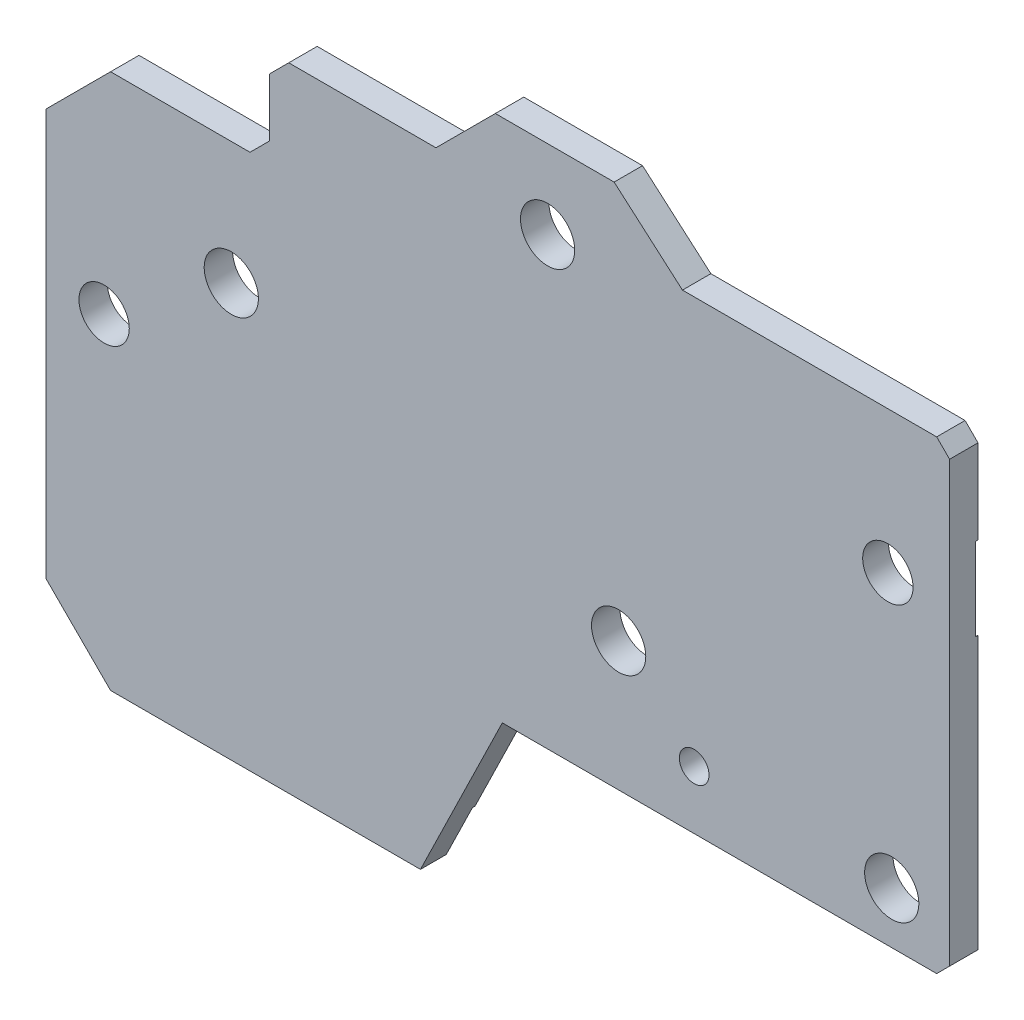
SolidWorks part; units mm, degrees
ref_plane "정면" through (0, 0, 0) normal (0, 0, 1) x (1, 0, 0)
ref_plane "윗면" through (0, 0, 0) normal (0, 1, 0) x (1, 0, 0)
ref_plane "우측면" through (0, 0, 0) normal (1, 0, 0) x (0, 0, -1)
sketch "스케치1" plane through (0, 0, 0) normal (0, 0, 1) x (1, 0, 0)
  line L0 (36.5, 0) -> (42.8405, 13)
  line L1 (42.3, 53.6) -> (51.5, 53.6)
  line L2 (0, 37.1) -> (0, 0)
  line L3 (0, 0) -> (36.5, 0)
  line L4 (72.0417, 49) -> (77.4805, 49)
  line L5 (42.8405, 13) -> (77.4805, 13)
  line L6 (77.4805, 49) -> (77.4805, 43.5612)
  line L8 (11.9, 49) -> (0, 37.1)
  line L9 (72.0417, 49) -> (77.4805, 43.5612) construction
  line L10 (42.3, 53.6) -> (37.7, 49)
  line L11 (37.7, 49) -> (11.9, 49)
  line L12 (51.5, 53.6) -> (56.7917, 49)
  line L13 (56.7917, 49) -> (72.0417, 49)
  line L14 (56.7917, 49) -> (11.9, 49) construction
  line L17 (77.4805, 13) -> (77.4805, 43.5612)
  circle A0 centre (21.85, 32) radius 2.1
  circle A1 centre (46.35, 47.5) radius 2.1
  circle A2 centre (51.85, 23) radius 2.1
  circle A3 centre (12, 25) radius 4.2
  circle A4 centre (12, 25) radius 2.5
  circle A5 centre (57.7, 17.5) radius 2.7
  circle A6 centre (57.7, 17.5) radius 1.15
  circle A7 centre (73, 17) radius 2.1
  point P0 (-1.1998, -0.6969)
  dimension "D1" = 4.2
  dimension "D2" = 4.2
  dimension "D3" = 4.2
  dimension "D9" = 2.3
  dimension "D10" = 5.4
  dimension "D11" = 5
  dimension "D12" = 8.4
  dimension "D13" = 12
  dimension "D31" = 4.2
  dimension "D4" = 24.5
  dimension "D5" = 24.5
  dimension "D6" = 30
  dimension "D7" = 15.5
  dimension "D8" = 9
  dimension "D14" = 25
  dimension "D15" = 34.64
  dimension "D16" = 135
  dimension "D17" = 13
  dimension "D18" = 49
  dimension "D19" = 4.6
  dimension "D20" = 9.2
  dimension "D21" = 41
  dimension "D22" = 15.25
  dimension "D23" = 57.7
  dimension "D24" = 37.1
  dimension "D25" = 135
  dimension "D26" = 17.5
  dimension "D27" = 25.8
  dimension "D28" = 135
  dimension "D29" = 36.5
  dimension "D30" = 116
  dimension "D32" = 32
  dimension "D33" = 21.85
  dimension "D34" = 73
  dimension "D35" = 17
extrude "보스-돌출1" add sketch "스케치1" along normal blind 3.2
sketch "스케치3" plane through (0, 0, 3.2) normal (0, 0, 1) x (1, 0, 0)
  circle A0 centre (12, 25) radius 4.2 construction
  circle A1 centre (12, 25) radius 4.2
  circle A2 centre (12, 25) radius 1.95
  circle A3 centre (57.7, 17.5) radius 2.7 construction
  circle A4 centre (57.7, 17.5) radius 2.7
  circle A5 centre (57.7, 17.5) radius 1.15
  dimension "D1" = 3.9
  dimension "D2" = 2.3
extrude "보스-돌출3" add sketch "스케치3" against normal blind 3.2
sketch "스케치6" plane through (0, 0, 3.2) normal (0, 0, 1) x (1, 0, 0)
  line L0 (44.2587, 8.0587) -> (101.1413, 8.0587) construction
  line L1 (102.1413, 9.0587) -> (102.1413, 65.9413) construction
  line L2 (101.1413, 66.9413) -> (72.7, 66.9413) construction
  line L3 (43.2587, 9.0587) -> (43.2587, 37.5) construction
  line L6 (37.7, 49) -> (11.9, 49) construction
  line L7 (0, 37.1) -> (0, 0) construction
  arc A0 (72.7, 66.9413) -> (43.2587, 37.5) centre (72.7, 37.5) ccw construction
  arc A1 (44.2587, 8.0587) -> (43.2587, 9.0587) centre (44.2587, 9.0587) cw construction
  arc A2 (101.1413, 8.0587) -> (102.1413, 9.0587) centre (101.1413, 9.0587) ccw construction
  arc A3 (102.1413, 65.9413) -> (101.1413, 66.9413) centre (101.1413, 65.9413) ccw construction
  dimension "D1" = 1
  dimension "D2" = 72.7
  dimension "D3" = 11.5
sketch "스케치7" plane through (0, 0, 0) normal (0, 0, -1) x (-1, 0, 0)
  circle A8 centre (-35, 4) radius 2.5
  circle A9 centre (-36.9, 49) radius 2.5
  circle A15 centre (-35, 4) radius 2.65
  dimension "D2" = 5
  dimension "D5" = 5
extrude "컷-돌출1" cut sketch "스케치7" against normal blind 1
chamfer "모따기1" distance 1 angle 45 1 edges at (0, 0, 2.1)
sketch "스케치11" plane through (0, 0, 3.2) normal (0, 0, 1) x (1, 0, 0)
  point P1 (72.7, 37.5)
  point P2 (57.7, 17.5)
  point P3 (12, 25)
chamfer "모따기3" distance 1 angle 45 1 edges at (77.4805, 13, 2.1)
sketch "스케치12" plane through (0, 0, 1) normal (0, 0, -1) x (-1, 0, 0)
  circle A0 centre (-6.5, 5) radius 2.1 construction
  circle A1 centre (-72.7, 38) radius 1.95
  dimension "D3" = 4.2
  dimension "D4" = 3.9
  dimension "D1" = 6.5
  dimension "D2" = 5
  dimension "D5" = 72.7
  dimension "D6" = 38
extrude "컷-돌출2" cut sketch "스케치12" against normal blind 10
sketch "스케치13" plane through (0, 0, 0) normal (0, 0, 1) x (1, 0, 0)
  line L0 (24.8, 49) -> (24.8, 41.5)
  line L1 (24.8, 41.5) -> (0, 41.5)
  line L2 (0, 41.5) -> (0, 49)
  line L3 (0, 49) -> (24.8, 49)
  line L4 (11.9, 49) -> (37.7, 49) construction
  dimension "D1" = 7.5
extrude "컷-돌출3" cut sketch "스케치13" along normal blind 10
chamfer "모따기4" distance 1.5 angle 45 2 edges at (24.8, 49, 2.1) (24.8, 41.5, 2.1)
sketch "스케치14" plane through (0, 0, 1) normal (0, 0, -1) x (-1, 0, 0)
  circle A0 centre (-6.5, 5) radius 5.05
  dimension "D1" = 10.1
  dimension "D2" = 6.5
  dimension "D3" = 5
extrude "컷-돌출4" [suppressed] cut sketch "스케치14" against normal blind 1.1
sketch "스케치15" plane through (0, 0, 1) normal (0, 0, -1) x (-1, 0, 0)
  line L0 (-72.7, 42.3) -> (-76, 42.3)
  line L1 (-77, 41.3) -> (-77, 34.7)
  line L2 (-76, 33.7) -> (-69.4, 33.7)
  line L3 (-68.4, 34.7) -> (-68.4, 38)
  circle A0 centre (-36.9, 45.7) radius 2.55
  arc A1 (-72.7, 42.3) -> (-68.4, 38) centre (-72.7, 38) cw
  arc A2 (-69.4, 33.7) -> (-68.4, 34.7) centre (-69.4, 34.7) ccw
  arc A3 (-77, 34.7) -> (-76, 33.7) centre (-76, 34.7) ccw
  arc A4 (-77, 41.3) -> (-76, 42.3) centre (-76, 41.3) cw
  dimension "D1" = 5.1
  dimension "D4" = 4.3
  dimension "D5" = 1
  dimension "D2" = 45.7
  dimension "D3" = 36.9
  dimension "D6" = 8.6
  dimension "D7" = 4.3
extrude "컷-돌출5" cut sketch "스케치15" against normal blind 0.2
chamfer "모따기5" distance 1 angle 45 1 edges at (77.4805, 49, 2.1)
sketch "스케치16" plane through (0, 0, 1) normal (0, 0, -1) x (-1, 0, 0)
  line L0 (-61.2, 19.8105) -> (-61.2, 28.7105)
  line L1 (-76.4805, 13) -> (-42.8405, 13) construction
  line L2 (-61.2, 28.7105) -> (-77.4805, 41.4856)
  line L3 (-77.4805, 48) -> (-77.4805, 14) construction
  line L4 (-77.4805, 41.4856) -> (-77.4805, 35.0856)
  line L5 (-77.4805, 35.0856) -> (-64.5, 24.9)
  line L6 (-64.5, 24.9) -> (-64.5, 16)
  line L7 (-61.5, 13) -> (-61.2, 13)
  line L8 (-38.5241, 4.15) -> (-34.3741, 4.15)
  line L9 (-42.8405, 13) -> (-36.5, 0) construction
  line L10 (-34.3741, 4.15) -> (-33.8864, 3.15)
  line L11 (-33.8864, 3.15) -> (-32.8864, 3.15)
  line L12 (-32.8864, 3.15) -> (-31.35, 0)
  line L13 (-36.5, 0) -> (-1, 0) construction
  line L14 (-31.35, 0) -> (-36.5, 0)
  line L15 (-36.5, 0) -> (-38.5241, 4.15)
  line L16 (-61.2, 19.8105) -> (-58.8, 19.8105)
  line L17 (-54.8, 17.65) -> (-54.8, 13)
  line L18 (-54.8, 13) -> (-61.2, 13)
  line L19 (-61.5, 13) -> (-64.5, 16)
  line L20 (-64.5, 16) -> (-64.5, 13) construction
  line L21 (-61.5, 13) -> (-64.5, 13) construction
  arc A0 (-58.8, 19.8105) -> (-54.8, 17.65) centre (-58.8, 15.0275) cw
  dimension "D1" = 3.3
  dimension "D2" = 6.4
  dimension "D3" = 4.15
  dimension "D4" = 5.15
  dimension "D5" = 1
  dimension "D6" = 1
  dimension "D7" = 64.5
  dimension "D8" = 11.9
  dimension "D9" = 6.4
  dimension "D10" = 2.4
  dimension "D11" = 8.9
  dimension "D12" = 4.65
  dimension "D13" = 3
  dimension "D14" = 3
extrude "컷-돌출6" cut sketch "스케치16" against normal blind 0.2
sketch "스케치17" plane through (0, 0, 0) normal (0, 0, 1) x (1, 0, 0)
  line L1 (-10.2296, 61.925) -> (7.5, 61.925)
  line L2 (-10.2296, 61.925) -> (-10.2296, -8.8404)
  line L3 (-10.2296, -8.8404) -> (7.5, -8.8404)
  line L4 (7.5, 61.925) -> (7.5, -8.8404)
  dimension "D1" = 7.5
extrude "컷-돌출7" cut sketch "스케치17" along normal blind 10
chamfer "모따기6" distance 5 angle 45 2 edges at (7.5, 0, 2.1) (7.5, 41.5, 2.1)
